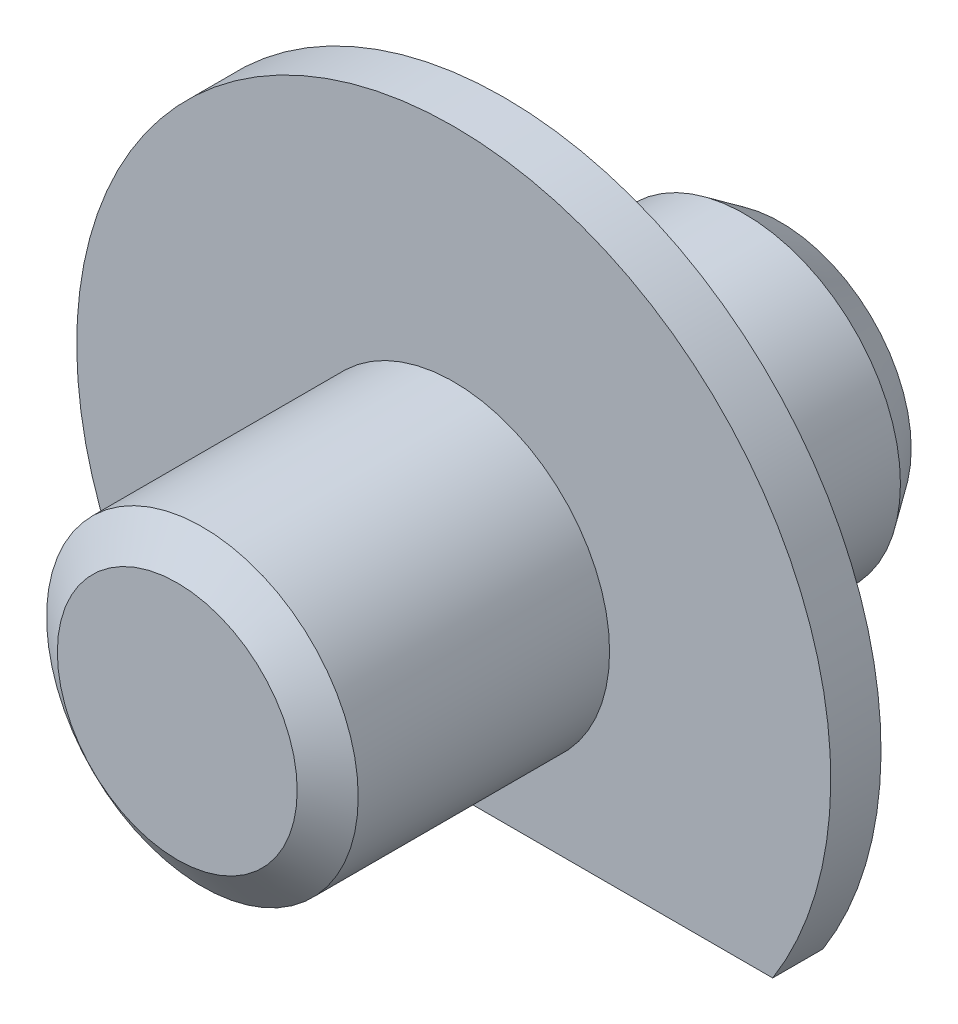
SolidWorks part; units mm, degrees
ref_plane "Front Plane" through (0, 0, 0) normal (0, 0, 1) x (1, 0, 0)
ref_plane "Top Plane" through (0, 0, 0) normal (0, 1, 0) x (1, 0, 0)
ref_plane "Right Plane" through (0, 0, 0) normal (1, 0, 0) x (0, 0, -1)
sketch "Sketch1" plane through (0, 0, 0) normal (0, 0, 1) x (1, 0, 0)
  circle A0 centre (0, 0) radius 3.1
  dimension "D1" = 6.2
extrude "Boss-Extrude1" add sketch "Sketch1" along normal blind 12
chamfer "Chamfer1" distance 0.5 angle 55 2 edges at (3.1, 0, 0) (3.1, 0, 12)
ref_plane "Plane1" through (0, 0, 6) normal (0, 0, 1) x (1, 0, 0)
sketch "Sketch2" plane through (0, 0, 6) normal (0, 0, 1) x (1, 0, 0)
  line L0 (-6.3443, -4) -> (6.3443, -4)
  line L1 (55, 0) -> (-55, 0) construction
  arc A0 (6.3443, -4) -> (-6.3443, -4) centre (0, 0) ccw
  circle A1 centre (0, 0) radius 2.3859 construction
  dimension "D1" = 15
  dimension "D2" = 4
extrude "Boss-Extrude2" add sketch "Sketch2" along normal blind 0.5 and the other way blind 0.5
